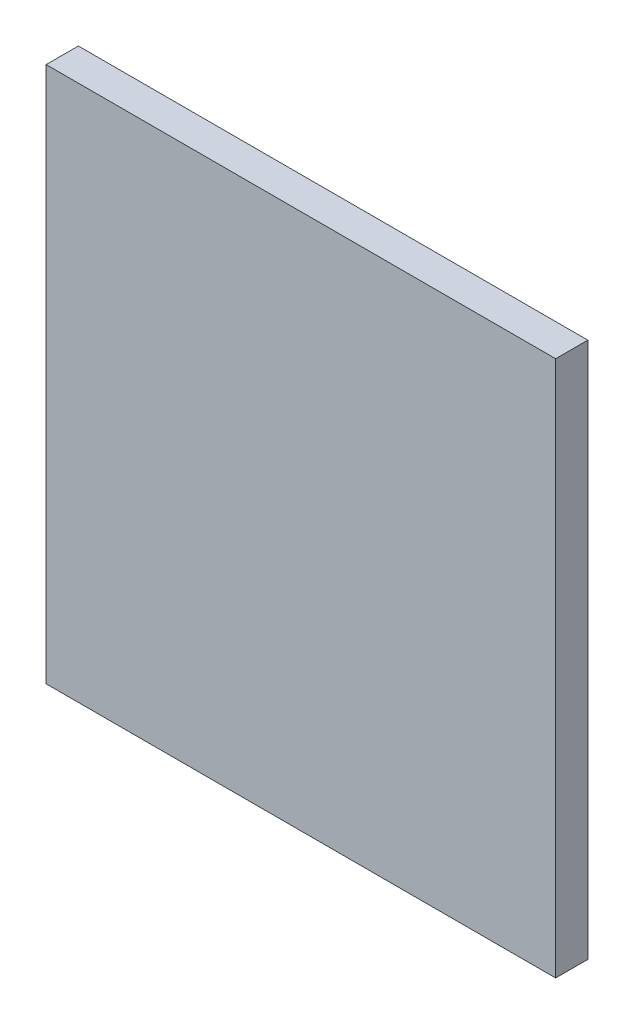
SolidWorks part; units mm, degrees
ref_plane "正面" through (0, 0, 0) normal (0, 0, 1) x (1, 0, 0)
ref_plane "平面" through (0, 0, 0) normal (0, 1, 0) x (1, 0, 0)
ref_plane "右側面" through (0, 0, 0) normal (1, 0, 0) x (0, 0, -1)
sketch "ｽｹｯﾁ1" plane through (0, 0, 0) normal (0, 0, 1) x (1, 0, 0)
  line L1 (9.5, -10) -> (-9.5, -10)
  line L2 (9.5, -10) -> (9.5, 10)
  line L3 (9.5, 10) -> (-9.5, 10)
  line L4 (-9.5, -10) -> (-9.5, 10)
  line L5 (9.5, -10) -> (-9.5, 10) construction
  line L6 (9.5, 10) -> (-9.5, -10) construction
  point P0 (0, 0)
  dimension "D1" = 19
  dimension "D2" = 20
extrude "ﾎﾞｽ - 押し出し1" add sketch "ｽｹｯﾁ1" along normal blind 1.2
